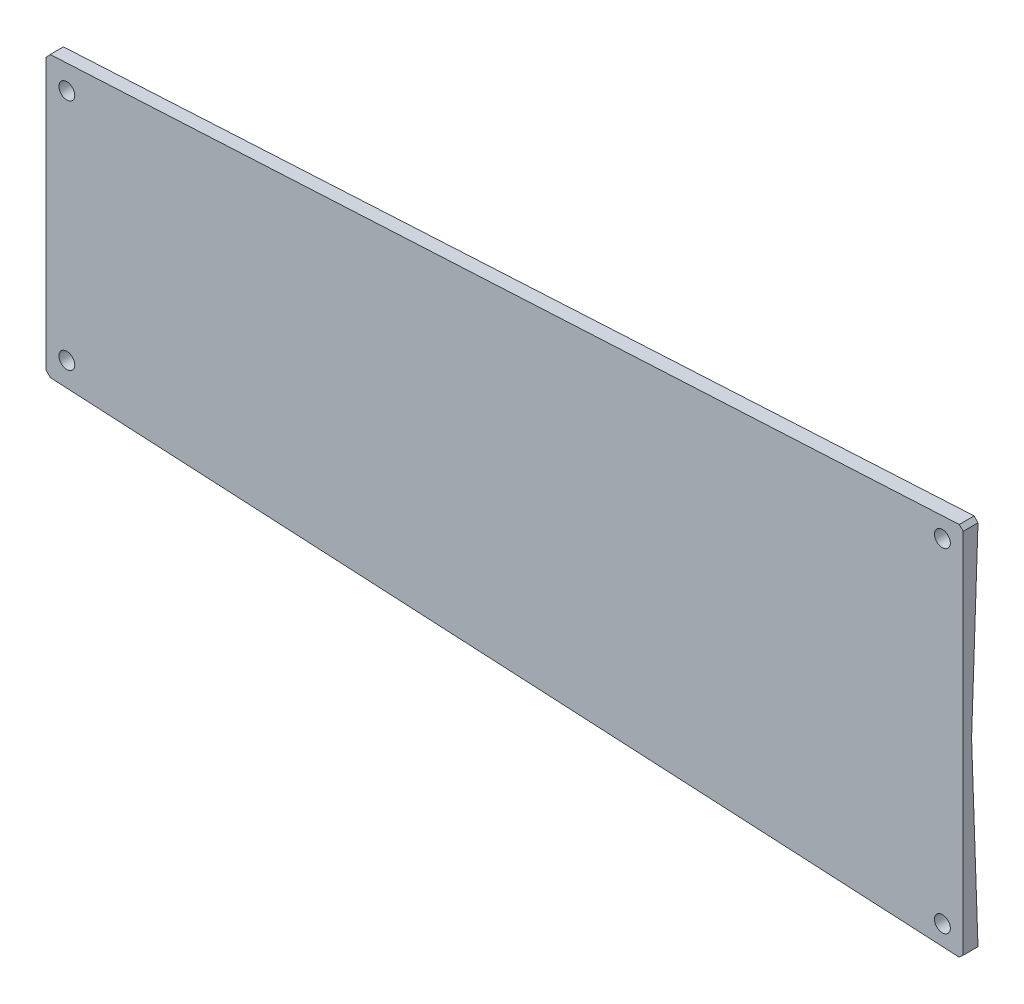
SolidWorks part; units mm, degrees
material "ABS PC"
ref_plane "Plan de face" through (0, 0, 0) normal (0, 0, 1) x (1, 0, 0)
ref_plane "Plan de dessus" through (0, 0, 0) normal (0, 1, 0) x (1, 0, 0)
ref_plane "Plan de droite" through (0, 0, 0) normal (1, 0, 0) x (0, 0, -1)
sketch "Esquisse1" plane through (0, 0, 0) normal (0, 0, 1) x (1, 0, 0)
  line L0 (-316.2957, 0) -> (148.2904, 0) construction
  line L1 (32.8928, 0) -> (32.8928, 45)
  line L2 (32.8928, 45) -> (-187.1072, 33.5)
  line L3 (-187.1072, 33.5) -> (-187.1072, 0)
  line L4 (32.8928, 0) -> (-187.1072, 0)
  circle A0 centre (-182.1072, 28) radius 1.9
  circle A1 centre (27.8928, 40) radius 1.9
  dimension "D4" = 5
  dimension "D1" = 45
  dimension "D2" = 220
  dimension "D3" = 33.5
  dimension "D5" = 5.5
  dimension "D6" = 5
  dimension "D7" = 5
extrude "Extrusion1" add sketch "Esquisse1" along normal blind 2
draft "Dépouille2" type of draft neutral plane draft angle 2 faces to draft 1 face at (-180.2072, 28, 0) neutral plane through (32.8928, 0, 2) neutral plane normal (0, -1, 0) parameters "D1"=2
mirror "Symétrie1" about plane through (32.8928, 0, 2) normal (0, 1, 0) of bodies 101
chamfer "Chanfrein1" distance 1 angle 45 1 edges at (-187.1072, 33.5, 0.4151)
chamfer "Chanfrein2" distance 1 angle 45 1 edges at (-187.1072, -33.5, 0.4151)
chamfer "Chanfrein4" distance 1 angle 45 1 edges at (32.8928, -45, 0.2143)
chamfer "Chanfrein5" distance 1 angle 45 1 edges at (32.8928, 45, 0.2143)
